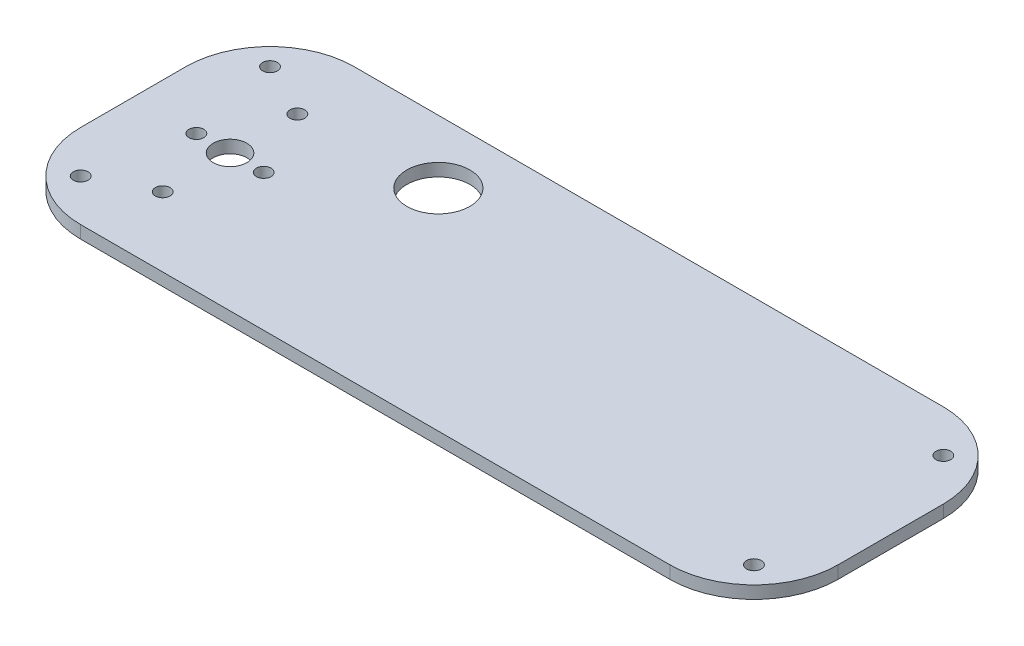
SolidWorks part; units mm, degrees
ref_plane "Alzado" through (0, 0, 0) normal (0, 0, 1) x (1, 0, 0)
ref_plane "Planta" through (0, 0, 0) normal (0, 1, 0) x (1, 0, 0)
ref_plane "Vista lateral" through (0, 0, 0) normal (1, 0, 0) x (0, 0, -1)
sketch "Croquis1" plane through (0, 0, 0) normal (0, 1, 0) x (1, 0, 0)
  line L1 (-90, -32.5) -> (90, -32.5)
  line L2 (-90, -32.5) -> (-90, 32.5)
  line L3 (-90, 32.5) -> (90, 32.5)
  line L4 (90, -32.5) -> (90, 32.5)
  line L5 (-90, -32.5) -> (90, 32.5) construction
  line L6 (-90, 32.5) -> (90, -32.5) construction
  point P0 (0, 0)
  dimension "D1" = 180
  dimension "D2" = 65
extrude "Saliente-Extruir1" add sketch "Croquis1" along normal blind 3
fillet "Redondeo1" radius 20 4 edges at (-90, 1.5, 32.5) (-90, 1.5, -32.5) (90, 1.5, -32.5) (90, 1.5, 32.5)
sketch "Croquis2" plane through (0, 3, 0) normal (0, 1, 0) x (1, 0, 0)
  line L0 (-90, 12.5) -> (-90, -12.5) construction
  line L1 (70, 32.5) -> (-70, 32.5) construction
  line L2 (-70, -32.5) -> (70, -32.5) construction
  line L3 (90, -12.5) -> (90, 12.5) construction
  circle A0 centre (-80, 22.5) radius 1.75
  circle A1 centre (-80, -22.5) radius 1.75
  circle A2 centre (80, -22.5) radius 1.75
  circle A3 centre (80, 22.5) radius 1.75
  dimension "D1" = 3.5
  dimension "D2" = 3.5
  dimension "D3" = 3.5
  dimension "D4" = 3.5
  dimension "D5" = 10
  dimension "D6" = 10
  dimension "D7" = 10
  dimension "D8" = 10
  dimension "D9" = 10
  dimension "D10" = 10
  dimension "D11" = 10
  dimension "D12" = 10
extrude "Cortar-Extruir1" cut sketch "Croquis2" against normal blind 3
sketch "Croquis3" plane through (0, 0, 0) normal (0, -1, 0) x (1, 0, 0)
  line L0 (-90, -12.5) -> (-90, 12.5) construction
  line L1 (-75, 0) -> (-59, 0)
  line L2 (-67, -16) -> (-67, 16)
  circle A0 centre (-67, 0) radius 4
  circle A1 centre (-59, 0) radius 1.75
  circle A2 centre (-75, 0) radius 1.75
  circle A3 centre (-67, 16) radius 1.75
  circle A4 centre (-67, -16) radius 1.75
  point P8 (-67, 0)
  point P13 (-67, 0)
  dimension "D2" = 8
  dimension "D4" = 3.5
  dimension "D5" = 3.5
  dimension "D7" = 3.5
  dimension "D8" = 3.5
  dimension "D1" = 23
  dimension "D3" = 16
  dimension "D6" = 32
extrude "Cortar-Extruir2" cut sketch "Croquis3" against normal blind 3
sketch "Croquis4" plane through (0, 0, 0) normal (0, -1, 0) x (1, 0, 0)
  line L0 (70, -32.5) -> (-70, -32.5) construction
  line L1 (-90, -12.5) -> (-90, 12.5) construction
  circle A0 centre (-35, -17.5) radius 7.5
  dimension "D1" = 15
  dimension "D3" = 55
  dimension "D2" = 15
extrude "Cortar-Extruir3" cut sketch "Croquis4" against normal blind 200
